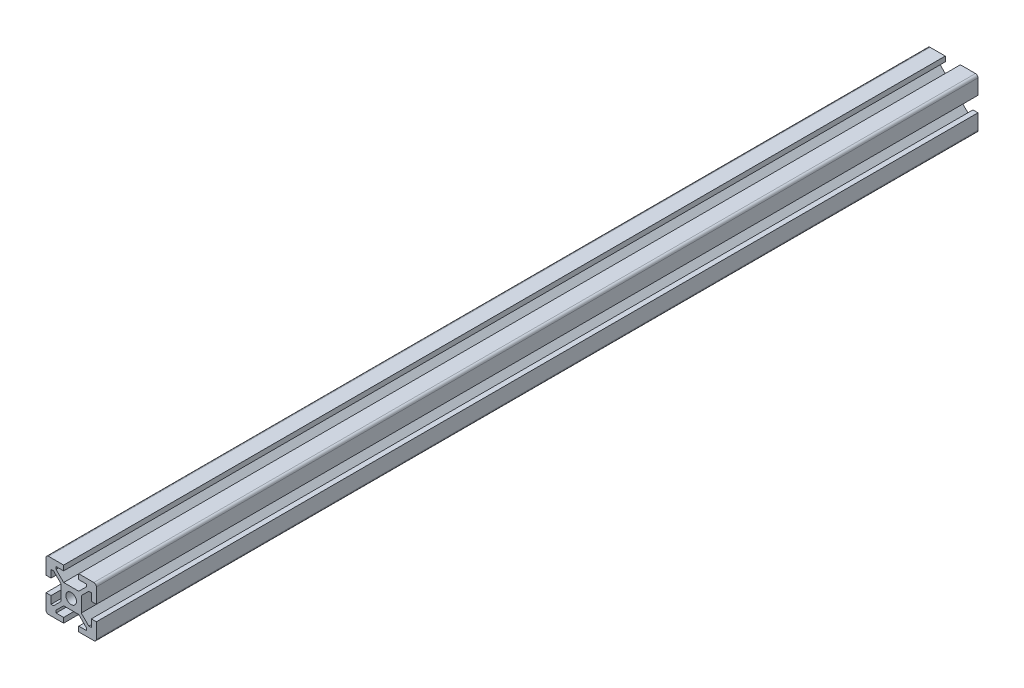
SolidWorks part; units mm, degrees
material "6063-O, Extruded Rod (SS)"
ref_plane "Piano frontale" through (0, 0, 0) normal (0, 0, 1) x (1, 0, 0)
ref_plane "Piano superiore" through (0, 0, 0) normal (0, 1, 0) x (1, 0, 0)
ref_plane "Piano destro" through (0, 0, 0) normal (1, 0, 0) x (0, 0, -1)
other "Lunghezza"
sketch "Schizzo1" plane through (0, 0, 0) normal (0, 0, 1) x (1, 0, 0)
  line L0 (-6, 8) -> (6, 8) construction
  line L1 (10, 3) -> (10, 10)
  line L2 (8, 3) -> (10, 3)
  line L3 (10, 10) -> (3, 10)
  line L4 (8, 6) -> (8, 3)
  line L5 (10, -10) -> (-10, 10) construction
  line L6 (10, 10) -> (-10, -10) construction
  line L7 (0, 23.5419) -> (0, -15.5419) construction
  line L8 (-13.4777, 0) -> (13.4408, 0) construction
  line L9 (-3, 4) -> (3, 4) construction
  line L10 (3, 4) -> (9, 10) construction
  line L11 (6, 11.4787) -> (6, 3.0667) construction
  line L12 (-6, 11.4787) -> (-6, 3.0667) construction
  line L13 (-3, 4) -> (-9, 10) construction
  line L14 (-3, 4) -> (-6, 7)
  line L15 (-6, 7) -> (-6, 8)
  line L16 (-6, 8) -> (-3, 8)
  line L17 (6, 8) -> (6, 7)
  line L18 (6, 7) -> (3, 4)
  line L19 (3, 4) -> (-3, 4)
  line L20 (-3, 8) -> (-3, 10)
  line L21 (6, 8) -> (3, 8)
  line L22 (3, 8) -> (3, 10)
  line L23 (-3, 10) -> (-10, 10)
  line L24 (7, 6) -> (8, 6)
  line L25 (4, 3) -> (7, 6)
  line L26 (4, -3) -> (4, 3)
  line L27 (7, -6) -> (4, -3)
  line L28 (8, -6) -> (7, -6)
  line L29 (8, -6) -> (8, -3)
  line L30 (8, -3) -> (10, -3)
  line L31 (10, -10) -> (10, -3)
  line L32 (3, -10) -> (10, -10)
  line L33 (3, -8) -> (3, -10)
  line L34 (6, -8) -> (3, -8)
  line L35 (6, -7) -> (6, -8)
  line L36 (3, -4) -> (6, -7)
  line L37 (-3, -4) -> (3, -4)
  line L38 (-6, -7) -> (-3, -4)
  line L39 (-6, -8) -> (-6, -7)
  line L40 (-6, -8) -> (-3, -8)
  line L41 (-3, -8) -> (-3, -10)
  line L42 (-10, -10) -> (-3, -10)
  line L43 (-10, -3) -> (-10, -10)
  line L44 (-8, -3) -> (-10, -3)
  line L45 (-8, -6) -> (-8, -3)
  line L46 (-7, -6) -> (-8, -6)
  line L47 (-4, -3) -> (-7, -6)
  line L48 (-4, 3) -> (-4, -3)
  line L49 (-7, 6) -> (-4, 3)
  line L50 (-8, 6) -> (-7, 6)
  line L51 (-8, 6) -> (-8, 3)
  line L52 (-8, 3) -> (-10, 3)
  line L53 (-10, 10) -> (-10, 3)
  circle A0 centre (0, 0) radius 2.1
  point P0 (0, 0)
  point P10 (0, 8)
  point P17 (0, 4)
  point P69 (0, 0)
  dimension "D6" = 4.2
  dimension "D1" = 20
  dimension "D2" = 10
  dimension "D3" = 2
  dimension "D4" = 12
  dimension "D5" = 4
  dimension "D7" = 4
  dimension "D8" = 6
  dimension "D9" = 6
  dimension "D10" = 3
  dimension "D11" = 4
extrude "Estrusione-Estrusione1" add sketch "Schizzo1" along normal blind 350
fillet "Raccordo1" radius 1 4 edges at (-10, -10, 175) (10, -10, 175) (-10, 10, 175) (10, 10, 175)
sketch "Sketch1" [suppressed] plane through (0, 0, 0) normal (1, 0, 0) x (0, 0, -1)
  line L0 (-150, 10) -> (-150, -10) construction
  line L1 (-300, 10) -> (0, 10) construction
  line L2 (0, -10) -> (-300, -10) construction
